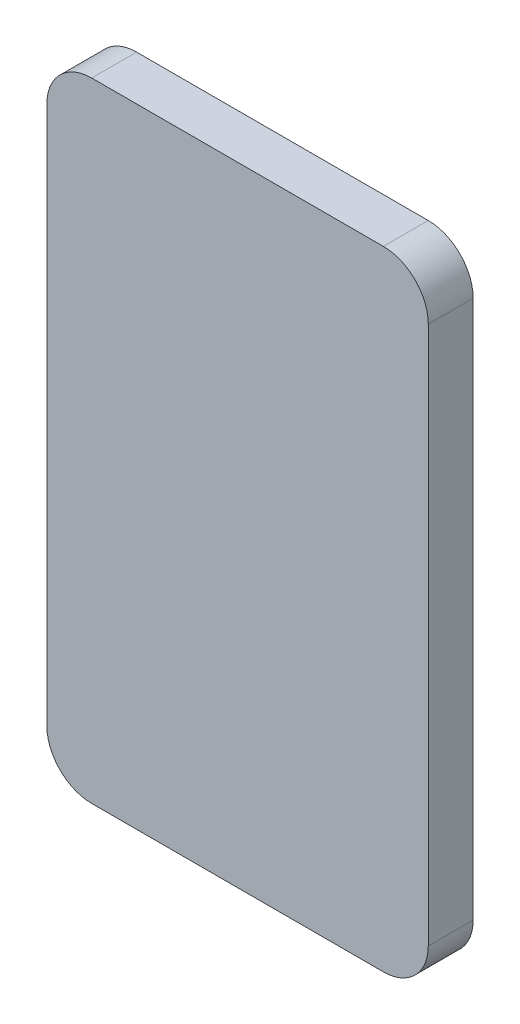
SolidWorks part; units mm, degrees
material "POLYURETHANE (11671)"
ref_plane "Płaszczyzna przednia" through (0, 0, 0) normal (0, 0, 1) x (1, 0, 0)
ref_plane "Płaszczyzna górna" through (0, 0, 0) normal (0, 1, 0) x (1, 0, 0)
ref_plane "Płaszczyzna prawa" through (0, 0, 0) normal (1, 0, 0) x (0, 0, -1)
sketch "Sketch1" plane through (0, 0, 0) normal (0, 0, 1) x (1, 0, 0)
  line L1 (0, 0) -> (17, 0)
  line L2 (0, 0) -> (0, 28)
  line L3 (0, 28) -> (17, 28)
  line L4 (17, 0) -> (17, 28)
  dimension "D1" = 28
  dimension "D2" = 17
extrude "Boss-Extrude1" add sketch "Sketch1" along normal blind 2
fillet "Fillet1" radius 2 4 edges at (17, 0, 1) (0, 0, 1) (0, 28, 1) (17, 28, 1)
